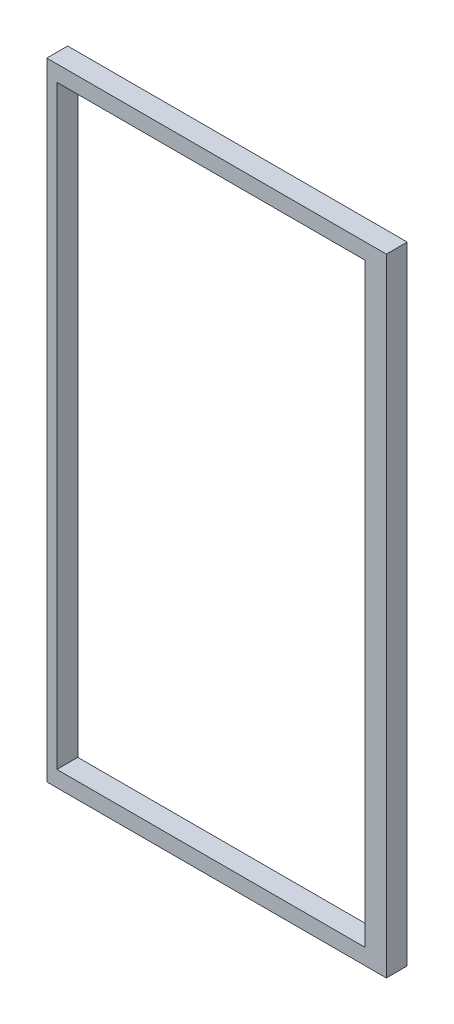
SolidWorks part; units mm, degrees
ref_plane "Front Plane" through (0, 0, 0) normal (0, 0, 1) x (1, 0, 0)
ref_plane "Top Plane" through (0, 0, 0) normal (0, 1, 0) x (1, 0, 0)
ref_plane "Right Plane" through (0, 0, 0) normal (1, 0, 0) x (0, 0, -1)
sketch "Sketch1" plane through (0, 0, 0) normal (0, 0, 1) x (1, 0, 0)
  line L1 (-21.2904, 60) -> (43.7096, 60)
  line L2 (-21.2904, 60) -> (-21.2904, -60)
  line L3 (-21.2904, -60) -> (43.7096, -60)
  line L4 (43.7096, 60) -> (43.7096, -60)
  line L7 (-19.3558, 56.9552) -> (39.6442, 56.9552)
  line L8 (-19.3558, 56.9552) -> (-19.3558, -56.9552)
  line L9 (-19.3558, -56.9552) -> (39.6442, -56.9552)
  line L10 (39.6442, 56.9552) -> (39.6442, -56.9552)
  point P0 (0, 0)
  point P6 (0, 0)
  dimension "D1" = 120
  dimension "D2" = 65
  dimension "D3" = 59
extrude "Boss-Extrude1" add sketch "Sketch1" along normal blind 4
